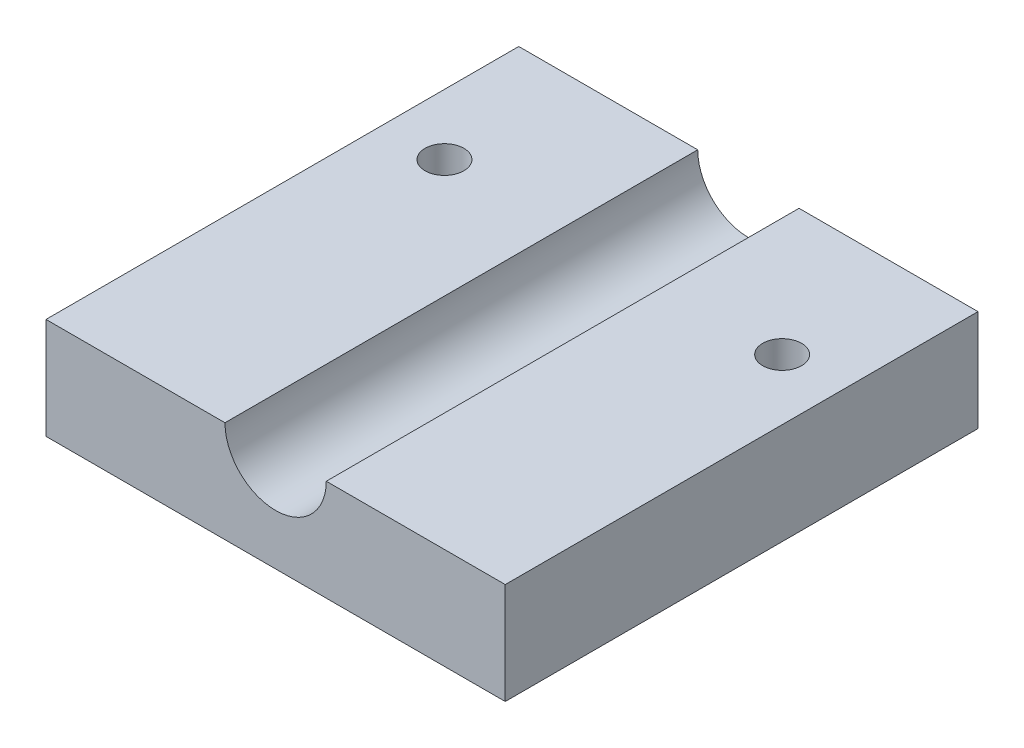
SolidWorks part; units mm, degrees
material "Nylon 6/10"
ref_plane "Front Plane" through (0, 0, 0) normal (0, 0, 1) x (1, 0, 0)
ref_plane "Top Plane" through (0, 0, 0) normal (0, 1, 0) x (1, 0, 0)
ref_plane "Right Plane" through (0, 0, 0) normal (1, 0, 0) x (0, 0, -1)
sketch "Sketch1" plane through (0, 0, 0) normal (0, 1, 0) x (1, 0, 0)
  line L1 (-21.59, -22.225) -> (21.59, -22.225)
  line L2 (-21.59, -22.225) -> (-21.59, 22.225)
  line L3 (-21.59, 22.225) -> (21.59, 22.225)
  line L4 (21.59, -22.225) -> (21.59, 22.225)
  line L5 (-21.59, -22.225) -> (21.59, 22.225) construction
  line L6 (-21.59, 22.225) -> (21.59, -22.225) construction
  point P0 (0, 0)
  dimension "D1" = 44.45
  dimension "D2" = 43.18
extrude "Boss-Extrude1" add sketch "Sketch1" along normal blind 9.525
sketch "Sketch4" plane through (0, 0, 22.225) normal (0, 0, 1) x (1, 0, 0)
  line L0 (-21.59, 9.525) -> (21.59, 9.525) construction
  circle A0 centre (0, 9.525) radius 4.7625
  dimension "D1" = 9.525
extrude "Cut-Extrude1" cut sketch "Sketch4" against normal through all
hole_wizard "MotorHoles" positions "Sketch3" profile "Sketch2" tap size "#4-40" standard "ANSI Inch"
sketch "Sketch3" plane through (0, 0, 0) normal (0, -1, 0) x (-1, 0, 0)
  line L0 (21.59, -22.225) -> (-21.59, -22.225) construction
  line L2 (0, 0) -> (0, -31.1437) construction
  point P0 (-5.715, -19.05)
  point P2 (5.715, -19.05)
  point P15 (13.081, 19.9644)
  point P17 (-13.081, 19.9644)
  dimension "D1" = 3.175
  dimension "D2" = 11.43
  dimension "D3" = 39.0144
  dimension "D4" = 7.366
  dimension "D5" = 7.366
cosmetic thread "Hole Thread1"
cosmetic thread "Hole Thread2"
sketch "Sketch2" plane through (5.715, 0, 19.05) normal (1, 0, 0) x (0, 0, -1)
  line L0 (0, 0) -> (0, 7.0292)
  line L1 (0, 7.0292) -> (1.1303, 6.35)
  line L2 (1.1303, 6.35) -> (1.1303, 0)
  line L5 (1.1303, 0) -> (0, 0)
  line L10 (0, 7.0292) -> (-1.1303, 6.35) construction
  line L11 (0, -6.35) -> (0, 107.95) construction
  dimension "Tap Drill Dia." = 2.2606
  dimension "Tap Drill Depth" = 6.35
  dimension "Drill Angle" = 118
cosmetic thread "Hole Thread5"
cosmetic thread "Hole Thread6"
hole_wizard "CBORE for #6 Socket Head Cap Screw1" positions "Sketch6" profile "Sketch5" counterbore size "#6" standard "ANSI Inch" end condition through all
sketch "Sketch6" plane through (0, 0, 0) normal (0, -1, 0) x (-1, 0, 0)
  line L0 (0, 0) -> (0, 20.3228) construction
  line L2 (-21.59, 22.225) -> (21.59, 22.225) construction
  point P0 (-15.875, 9.525)
  point P2 (15.875, 9.525)
  dimension "D1" = 31.75
  dimension "D2" = 12.7
sketch "Sketch5" plane through (15.875, 0, -9.525) normal (1, 0, 0) x (0, 0, -1)
  line L0 (0, 0) -> (0, 9.525)
  line L1 (0, 9.525) -> (1.8288, 9.525)
  line L3 (1.8288, 9.525) -> (1.8288, 3.5052)
  line L4 (1.8288, 3.5052) -> (3.5725, 3.5052)
  line L5 (3.5725, 3.5052) -> (3.5725, 0)
  line L7 (3.5725, 0) -> (0, 0)
  line L11 (0, -6.35) -> (0, 107.95) construction
  dimension "Thru Hole Dia." = 3.6576
  dimension "Thru Hole Depth" = 9.525
  dimension "C'Bore Dia." = 7.145
  dimension "C'Bore Depth" = 3.5052
chamfer "Chamfer1" [suppressed] distance 10.16 angle 45
hole_wizard "#4-40 Tapped Hole1" positions "Sketch8" profile "Sketch7" tap size "#4-40" standard "ANSI Inch"
sketch "Sketch8" plane through (0, 0, 0) normal (0, -1, 0) x (-1, 0, 0)
  line L0 (0, 0) -> (0, 3.4708) construction
  line L2 (-12.7, 9.525) -> (12.7, 9.525) construction
  circle A0 centre (-12.7, 9.525) radius 1.8288 construction
  circle A1 centre (12.7, 9.525) radius 1.8288 construction
  circle A2 centre (-12.7, 9.525) radius 1.8288 construction
  circle A3 centre (12.7, 9.525) radius 1.8288 construction
  point P0 (0, 9.525)
  point P2 (0, -5.715)
  dimension "D1" = 15.24
sketch "Sketch7" plane through (0, 0, -9.525) normal (1, 0, 0) x (0, 0, -1)
  line L0 (0, 0) -> (0, 9.525)
  line L1 (0, 9.525) -> (1.1303, 9.525)
  line L2 (1.1303, 9.525) -> (1.1303, 0)
  line L5 (1.1303, 0) -> (0, 0)
  line L11 (0, -6.35) -> (0, 107.95) construction
  dimension "Thru Tap Drill Dia." = 2.2606
  dimension "Thru Tap Drill Depth" = 9.525
cosmetic thread "Hole Thread3" [suppressed]
cosmetic thread "Hole Thread4" [suppressed]
chamfer "Chamfer3" [suppressed] distance 5.08 angle 45
